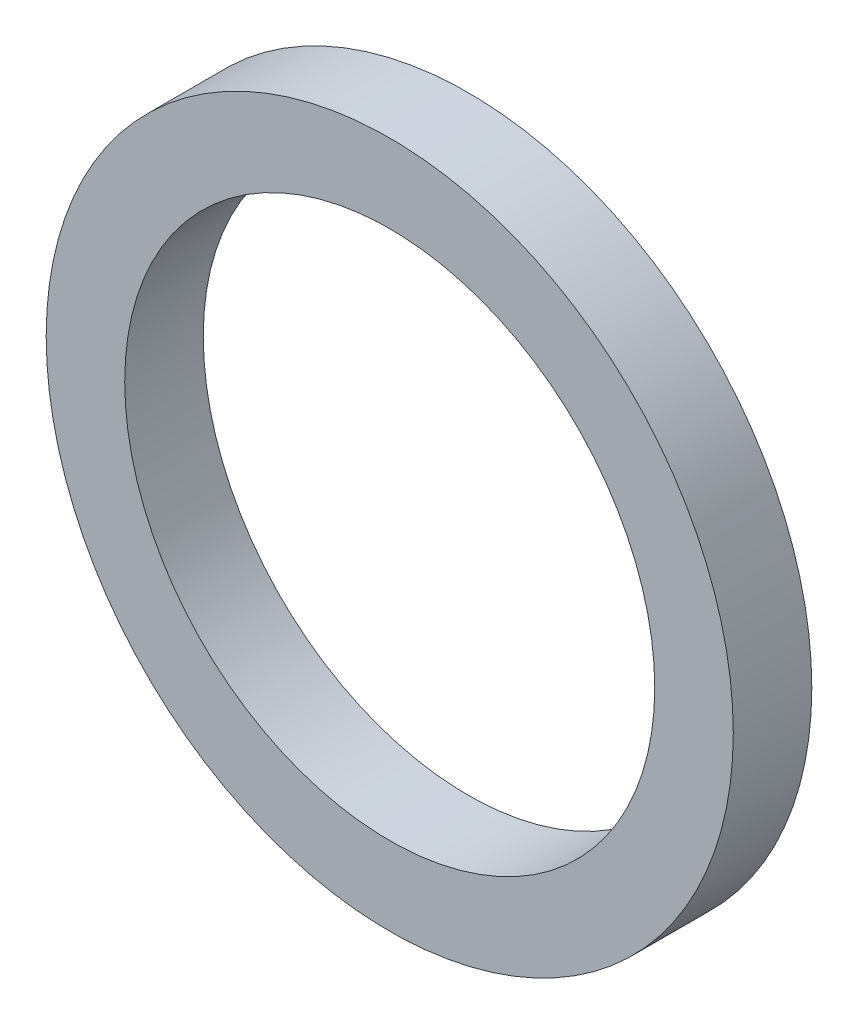
SolidWorks part; units mm, degrees
ref_plane "正面" through (0, 0, 0) normal (0, 0, 1) x (1, 0, 0)
ref_plane "平面" through (0, 0, 0) normal (0, 1, 0) x (1, 0, 0)
ref_plane "右側面" through (0, 0, 0) normal (1, 0, 0) x (0, 0, -1)
sketch "ｽｹｯﾁ1" plane through (0, 0, 0) normal (0, 0, 1) x (1, 0, 0)
  circle A0 centre (0, 0) radius 5.4
  circle A1 centre (0, 0) radius 7
  dimension "D1" = 10.8
  dimension "D2" = 14
extrude "ﾎﾞｽ - 押し出し1" add sketch "ｽｹｯﾁ1" along normal blind 1.6
